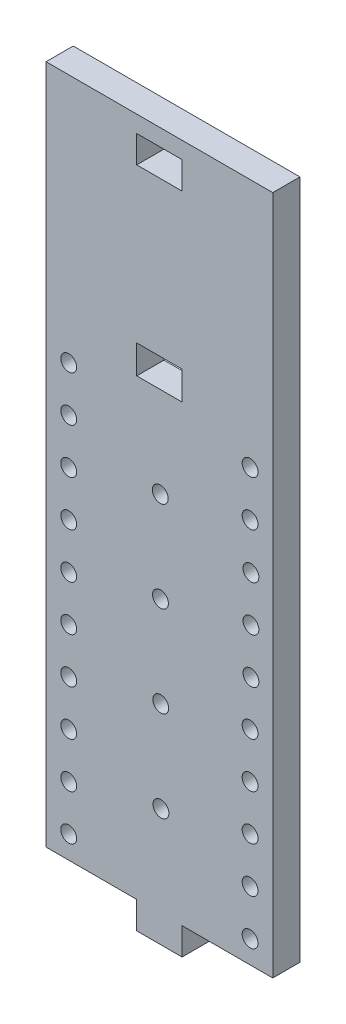
SolidWorks part; units mm, degrees
ref_plane "Plano frontal" through (0, 0, 0) normal (0, 0, 1) x (1, 0, 0)
ref_plane "Plano superior" through (0, 0, 0) normal (0, 1, 0) x (1, 0, 0)
ref_plane "Plano direito" through (0, 0, 0) normal (1, 0, 0) x (0, 0, -1)
sketch "Esboço1" plane through (0, 0, 0) normal (0, 0, 1) x (1, 0, 0)
  line L1 (24.6057, 0) -> (-25.3943, 0)
  line L2 (24.6057, 0) -> (24.6057, 150)
  line L3 (24.6057, 150) -> (-25.3943, 150)
  line L4 (-25.3943, 0) -> (-25.3943, 150)
  line L8 (24.6057, 127.5) -> (24.6057, 112.5) construction
  line L10 (-25.3943, 112.5) -> (-25.3943, 97.5) construction
  line L12 (24.6057, 97.5) -> (24.6057, 82.5) construction
  line L14 (-25.3943, 82.5) -> (-25.3943, 67.5) construction
  line L16 (24.6057, 67.5) -> (24.6057, 52.5) construction
  line L18 (-25.3943, 52.5) -> (-25.3943, 37.5) construction
  line L20 (24.6057, 37.5) -> (24.6057, 22.5) construction
  line L22 (-25.3943, 22.5) -> (-25.3943, 7.5) construction
  point P4 (-0.3943, 0)
  dimension "D1" = 150
  dimension "D2" = 50
extrude "Ressalto-extrusão1" add sketch "Esboço1" along normal blind 6
sketch "Esboço2" plane through (0, 0, 6) normal (0, 0, 1) x (1, 0, 0)
  line L0 (-20.3943, 149.6155) -> (-20.3943, -0.3845) construction
  line L1 (19.6057, 149.6155) -> (19.6057, -0.3845) construction
  line L2 (-25.3943, 150) -> (-25.3943, 0) construction
  line L3 (-25.3943, 0) -> (24.6057, 0) construction
  line L4 (24.6057, 0) -> (24.6057, 150) construction
  line L5 (-25.3943, 0) -> (24.6057, 0) construction
  line L6 (-25.3943, 80) -> (24.6057, 80) construction
  line L7 (24.6057, 60) -> (-25.3943, 60) construction
  line L8 (24.6057, 40) -> (-25.3943, 40) construction
  line L9 (24.6057, 20) -> (-25.3943, 20) construction
  line L10 (0, 0) -> (-0.3943, 150) construction
  line L11 (24.6057, 150) -> (-25.3943, 150) construction
  circle A0 centre (-20.3943, 95) radius 1.75
  circle A1 centre (-20.3943, 85) radius 1.75
  circle A2 centre (-20.3943, 75) radius 1.75
  circle A3 centre (-20.3943, 65) radius 1.75
  circle A4 centre (-20.3943, 55) radius 1.75
  circle A5 centre (-20.3943, 45) radius 1.75
  circle A6 centre (-20.3943, 35) radius 1.75
  circle A7 centre (-20.3943, 25) radius 1.75
  circle A8 centre (-20.3943, 15) radius 1.75
  circle A9 centre (-20.3943, 5) radius 1.75
  circle A10 centre (19.6057, 95) radius 1.75
  circle A11 centre (19.6057, 85) radius 1.75
  circle A12 centre (19.7931, 75) radius 1.75
  circle A13 centre (19.7931, 65) radius 1.75
  circle A14 centre (19.7931, 55) radius 1.75
  circle A15 centre (19.6057, 45) radius 1.75
  circle A16 centre (19.6057, 35) radius 1.75
  circle A17 centre (19.6057, 25) radius 1.75
  circle A18 centre (19.6057, 15) radius 1.75
  circle A19 centre (19.6057, 5) radius 1.75
  circle A20 centre (-0.0526, 20) radius 1.75
  circle A22 centre (-0.2103, 80) radius 1.75
  circle A23 centre (-0.1051, 40) radius 1.75
  circle A24 centre (-0.1577, 60) radius 1.75
  dimension "D1" = 3.5
  dimension "D2" = 3.5
  dimension "D3" = 3.5
  dimension "D4" = 3.5
  dimension "D5" = 3.5
  dimension "D6" = 3.5
  dimension "D7" = 3.5
  dimension "D8" = 3.5
  dimension "D9" = 3.5
  dimension "D10" = 3.5
  dimension "D20" = 3.5
  dimension "D21" = 3.5
  dimension "D22" = 3.5
  dimension "D23" = 3.5
  dimension "D24" = 3.5
  dimension "D25" = 3.5
  dimension "D26" = 3.5
  dimension "D27" = 3.5
  dimension "D28" = 3.5
  dimension "D29" = 3.5
  dimension "D31" = 3.5
  dimension "D32" = 3.5
  dimension "D33" = 3.5
  dimension "D34" = 3.5
  dimension "D47" = 5
  dimension "D48" = 5
  dimension "D49" = 5
  dimension "D50" = 5
  dimension "D11" = 10
  dimension "D12" = 10
  dimension "D13" = 10
  dimension "D14" = 10
  dimension "D15" = 10
  dimension "D16" = 10
  dimension "D17" = 10
  dimension "D18" = 10
  dimension "D19" = 10
  dimension "D30" = 10
  dimension "D35" = 5
  dimension "D36" = 5
  dimension "D37" = 5
  dimension "D38" = 5
  dimension "D39" = 10
  dimension "D40" = 10
  dimension "D41" = 10
  dimension "D42" = 10
  dimension "D43" = 10
  dimension "D44" = 10
  dimension "D45" = 10
  dimension "D46" = 10
extrude "Corte-extrusão1" cut sketch "Esboço2" against normal blind 6
sketch "Esboço3" plane through (0, 0, 0) normal (0, -1, 0) x (-1, 0, 0)
  line L0 (25.3943, -6) -> (-24.6057, -6) construction
  line L1 (5.3943, -6) -> (-4.6057, -6)
  line L2 (5.3943, -6) -> (5.3943, 0)
  line L3 (5.3943, 0) -> (-4.6057, 0)
  line L4 (-4.6057, -6) -> (-4.6057, 0)
  line L5 (25.3943, 0) -> (-24.6057, 0) construction
  line L6 (25.3943, -6) -> (25.3943, 0) construction
  line L7 (-24.6057, -6) -> (-24.6057, 0) construction
  dimension "D1" = 20
  dimension "D2" = 20
extrude "Ressalto-extrusão2" add sketch "Esboço3" along normal blind 6
sketch "Esboço4" plane through (0, 0, 6) normal (0, 0, 1) x (1, 0, 0)
  line L6 (-25.3943, 150) -> (-25.3943, 0) construction
  line L7 (-5.3943, 106.2954) -> (4.6057, 106.2954)
  line L8 (-5.3943, 106.2954) -> (-5.3943, 100)
  line L9 (-5.3943, 100) -> (4.6057, 100)
  line L10 (4.6057, 106.2954) -> (4.6057, 100)
  line L11 (24.6057, 0) -> (24.6057, 150) construction
  circle A1 centre (-20.3943, 95) radius 1.75 construction
  dimension "D1" = 5
  dimension "D2" = 20
  dimension "D3" = 20
extrude "Corte-extrusão2" cut sketch "Esboço4" against normal blind 6
sketch "Esboço5" plane through (0, 0, 6) normal (0, 0, 1) x (1, 0, 0)
  line L0 (-25.3943, 150) -> (-25.3943, 0) construction
  line L1 (-5.3943, 140.2954) -> (4.6057, 140.2954)
  line L2 (-5.3943, 140.2954) -> (-5.3943, 146.2954)
  line L3 (-5.3943, 146.2954) -> (4.6057, 146.2954)
  line L4 (4.6057, 140.2954) -> (4.6057, 146.2954)
  line L5 (24.6057, 0) -> (24.6057, 150) construction
  line L6 (4.6057, 106.2954) -> (-5.3943, 106.2954) construction
  dimension "D1" = 20
  dimension "D2" = 40
  dimension "D3" = 20
  dimension "D4" = 6
extrude "Corte-extrusão3" cut sketch "Esboço5" against normal blind 6
